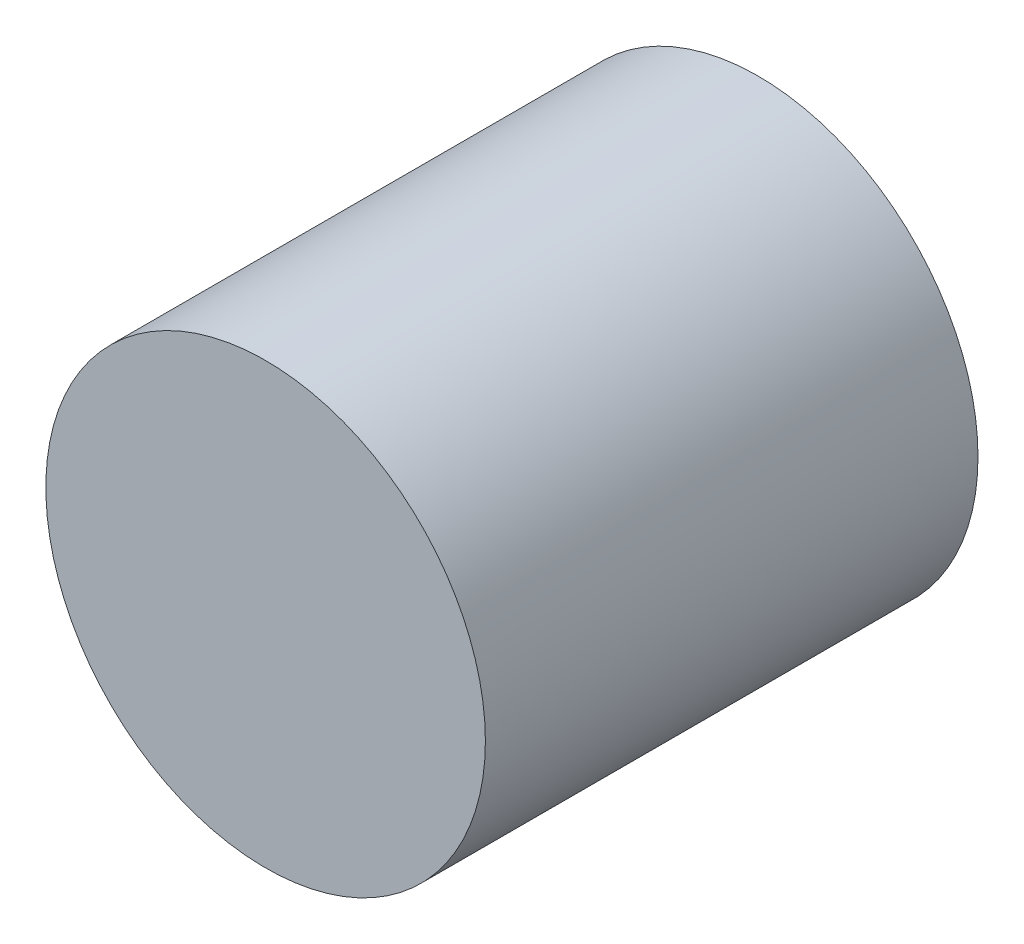
SolidWorks part; units mm, degrees
ref_plane "Płaszczyzna przednia" through (0, 0, 0) normal (0, 0, 1) x (1, 0, 0)
ref_plane "Płaszczyzna górna" through (0, 0, 0) normal (0, 1, 0) x (1, 0, 0)
ref_plane "Płaszczyzna prawa" through (0, 0, 0) normal (1, 0, 0) x (0, 0, -1)
sketch "Szkic1" plane through (0, 0, 0) normal (0, 0, 1) x (1, 0, 0)
  circle A0 centre (0, 0) radius 2.9
  dimension "D1" = 5.8
extrude "Dodanie-wyciągnięcie1" add sketch "Szkic1" along normal blind 6 contours A0
sketch "Szkic2" plane through (0, 0, 6) normal (0, 0, 1) x (1, 0, 0)
  circle A0 centre (0, 0) radius 1.6
  dimension "D1" = 3.2
extrude "Wytnij-wyciągnięcie1" cut sketch "Szkic2" against normal blind 6 contours A0
sketch "Szkic3" plane through (0, 0, 6) normal (0, 0, 1) x (1, 0, 0)
  circle A0 centre (0, 0) radius 2.9
extrude "Dodanie-wyciągnięcie2" add sketch "Szkic3" along normal blind 0.5 contours A0
